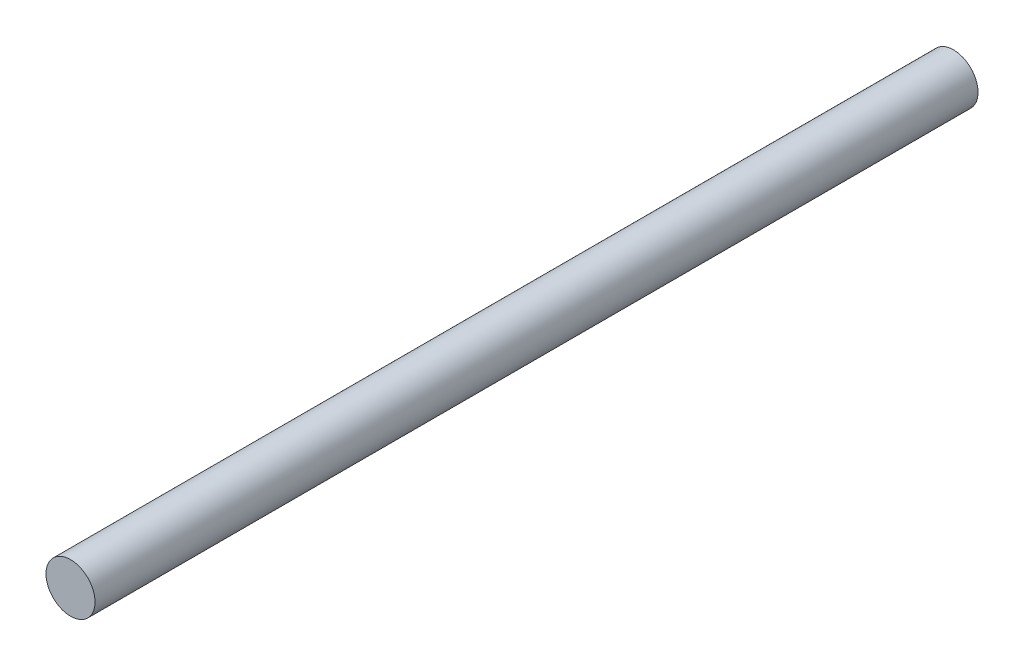
SolidWorks part; units mm, degrees
ref_plane "Front Plane" through (0, 0, 0) normal (0, 0, 1) x (1, 0, 0)
ref_plane "Top Plane" through (0, 0, 0) normal (0, 1, 0) x (1, 0, 0)
ref_plane "Right Plane" through (0, 0, 0) normal (1, 0, 0) x (0, 0, -1)
sketch "Sketch1" plane through (0, 0, 0) normal (0, 0, 1) x (1, 0, 0)
  circle A0 centre (0, 0) radius 2.5
  dimension "D1" = 5
extrude "Boss-Extrude1" add sketch "Sketch1" along normal blind 90
